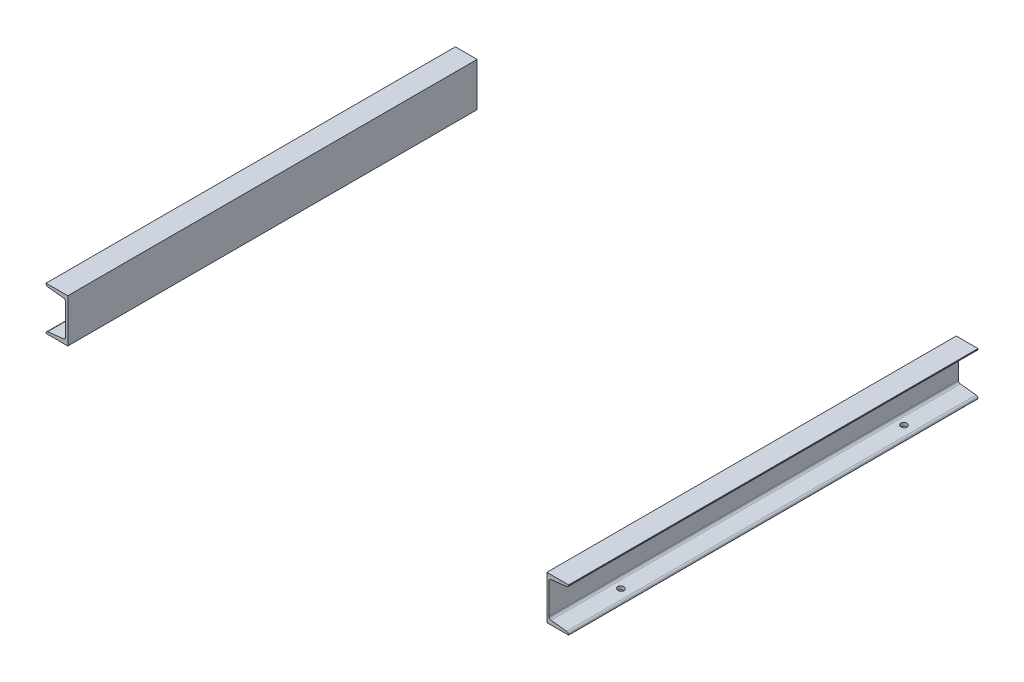
SolidWorks part; units mm, degrees
ref_plane "Front Plane" through (0, 0, 0) normal (0, 0, 1) x (1, 0, 0)
ref_plane "Top Plane" through (0, 0, 0) normal (0, 1, 0) x (1, 0, 0)
ref_plane "Right Plane" through (0, 0, 0) normal (1, 0, 0) x (0, 0, -1)
sketch "Sketch1" plane through (0, 0, 0) normal (0, 0, 1) x (1, 0, 0)
  line L0 (0, 0) -> (0, -50000) construction
  point P0 (-600, 0)
  point P4 (600, 0)
  line B0 (-600, 0) -> (-550, 0)
  line B1 (-595.5522, -5.4942) -> (-559.4478, -9.5058)
  line B2 (-550, 0) -> (-550, -100)
  line B3 (-555, -14.4752) -> (-555, -85.5248)
  line B4 (-550, -100) -> (-600, -100)
  line B5 (-559.4478, -90.4942) -> (-595.5522, -94.5058)
  line B6 (-600, 0) -> (-600, -0.5248)
  line B7 (-600, -100) -> (-600, -99.4752)
  arc B8 (-600, -0.5248) -> (-595.5522, -5.4942) centre (-595, -0.5248) ccw
  arc B9 (-559.4478, -90.4942) -> (-555, -85.5248) centre (-560, -85.5248) ccw
  arc B10 (-555, -14.4752) -> (-559.4478, -9.5058) centre (-560, -14.4752) ccw
  arc B11 (-595.5522, -94.5058) -> (-600, -99.4752) centre (-595, -99.4752) ccw
  line B12 (600, 0) -> (550, 0)
  line B13 (595.5522, -5.4942) -> (559.4478, -9.5058)
  line B14 (550, 0) -> (550, -100)
  line B15 (555, -14.4752) -> (555, -85.5248)
  line B16 (550, -100) -> (600, -100)
  line B17 (559.4478, -90.4942) -> (595.5522, -94.5058)
  line B18 (600, 0) -> (600, -0.5248)
  line B19 (600, -100) -> (600, -99.4752)
  arc B20 (600, -0.5248) -> (595.5522, -5.4942) centre (595, -0.5248) cw
  arc B21 (559.4478, -90.4942) -> (555, -85.5248) centre (560, -85.5248) cw
  arc B22 (555, -14.4752) -> (559.4478, -9.5058) centre (560, -14.4752) cw
  arc B23 (595.5522, -94.5058) -> (600, -99.4752) centre (595, -99.4752) cw
sketch_block_instance "A$C2FD70804-1"
sketch_block "A$C2FD70804"
sketch_block_instance "A$C2FD70804-2"
extrude "Boss-Extrude1" add sketch "Sketch1" along normal mid plane 940
sketch "Sketch2" plane through (0, -100, 0) normal (0, -1, 0) x (1, 0, 0)
  line L0 (0, 0) -> (-50000, 0) construction
  line L1 (-600, 470) -> (-550, 470) construction
  line L2 (-600, 470) -> (-600, -470) construction
  line L3 (0, 0) -> (0, -50000) construction
  circle A0 centre (-575, 325) radius 7
  circle A1 centre (-575, -325) radius 7
  circle A2 centre (575, -325) radius 7
  circle A3 centre (575, 325) radius 7
  dimension "D1" = 14
  dimension "D2" = 145
  dimension "D3" = 25
extrude "Cut-Extrude1" cut sketch "Sketch2" against normal blind 10
